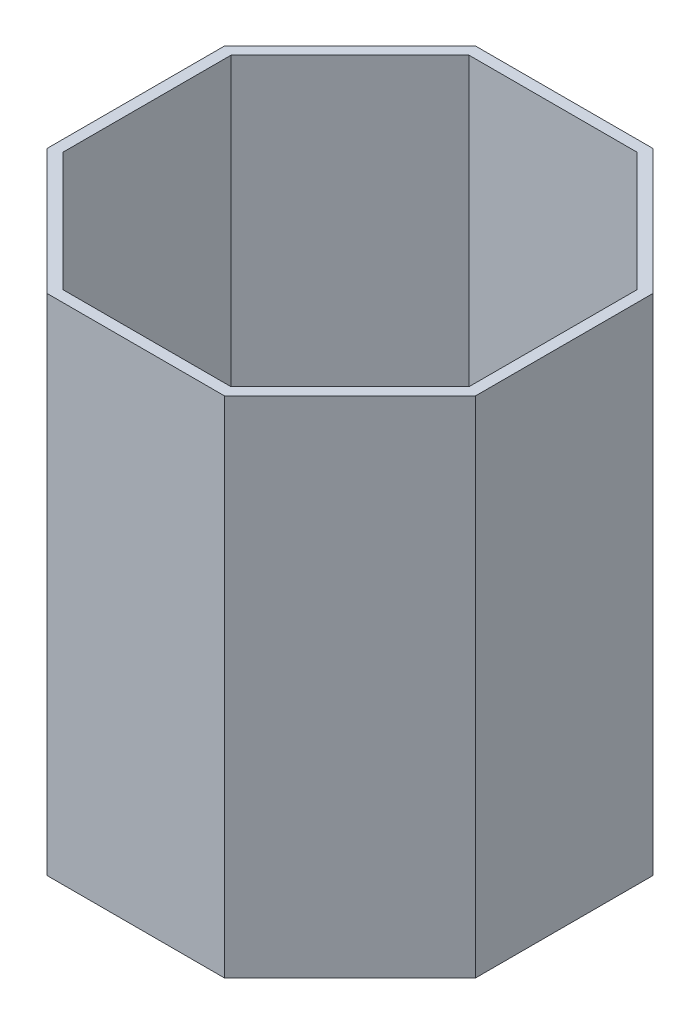
SolidWorks part; units mm, degrees
ref_plane "Front Plane" through (0, 0, 0) normal (0, 0, 1) x (1, 0, 0)
ref_plane "Top Plane" through (0, 0, 0) normal (0, 1, 0) x (1, 0, 0)
ref_plane "Right Plane" through (0, 0, 0) normal (1, 0, 0) x (0, 0, -1)
sketch "Sketch2" plane through (0, 0, 0) normal (0, 1, 0) x (1, 0, 0)
  line L9 (-76.5, 31.6873) -> (-76.5, -31.6873)
  line L10 (-72.5, -30.0305) -> (-30.0305, -72.5)
  line L22 (-30.0305, -72.5) -> (30.0305, -72.5)
  line L23 (30.0305, -72.5) -> (72.5, -30.0305)
  line L24 (72.5, -30.0305) -> (72.5, 30.0305)
  line L25 (72.5, 30.0305) -> (30.0305, 72.5)
  line L26 (30.0305, 72.5) -> (-30.0305, 72.5)
  line L27 (-30.0305, 72.5) -> (-72.5, 30.0305)
  line L28 (-72.5, 30.0305) -> (-72.5, -30.0305)
  line L29 (-76.5, -31.6873) -> (-31.6873, -76.5)
  line L30 (-31.6873, -76.5) -> (31.6873, -76.5)
  line L31 (31.6873, -76.5) -> (76.5, -31.6873)
  line L32 (76.5, -31.6873) -> (76.5, 31.6873)
  line L33 (76.5, 31.6873) -> (31.6873, 76.5)
  line L34 (31.6873, 76.5) -> (-31.6873, 76.5)
  line L35 (-31.6873, 76.5) -> (-76.5, 31.6873)
  circle A0 centre (0, 0) radius 72.5 construction
  point P1 (0, 0)
  point P12 (-72.5, 0)
  dimension "D1" = 145
  dimension "D2" = 4
extrude "Boss-Extrude4" add sketch "Sketch2" along normal blind 180
